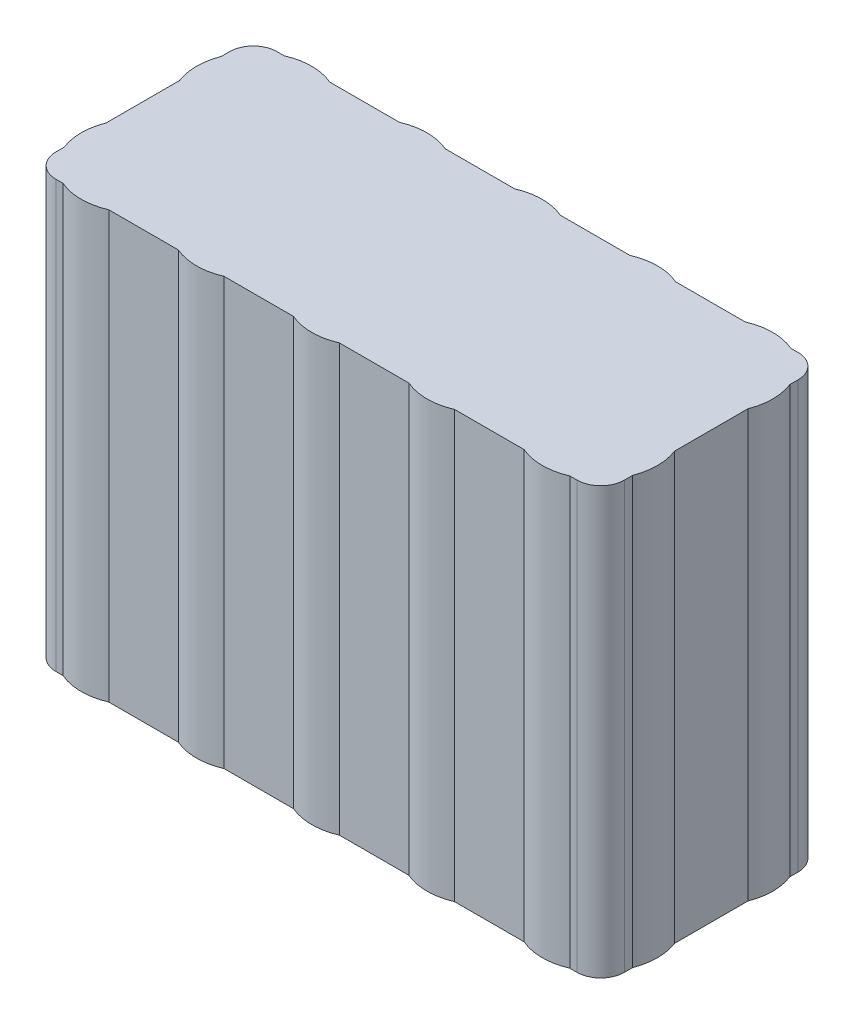
SolidWorks part; units mm, degrees
material "Gray Cast Iron"
ref_plane "Front" through (0, 0, 0) normal (0, 0, 1) x (1, 0, 0)
ref_plane "Top" through (0, 0, 0) normal (0, 1, 0) x (1, 0, 0)
ref_plane "Right" through (0, 0, 0) normal (1, 0, 0) x (0, 0, -1)
sketch "Sketch1" plane through (0, 0, 0) normal (0, 1, 0) x (1, 0, 0)
  line L0 (-27.8306, -10.7806) -> (30.5694, -10.7806) construction
  line L6 (-31.6306, -17.4806) -> (34.3694, -17.4806)
  line L7 (30.5694, -10.7806) -> (30.5694, 3.8194) construction
  line L8 (30.5694, 3.8194) -> (-27.8306, 3.8194) construction
  line L9 (-27.8306, 3.8194) -> (-27.8306, -10.7806) construction
  line L10 (-34.6306, -14.4806) -> (-34.6306, 7.5194)
  line L11 (-31.6306, 10.5194) -> (34.3694, 10.5194)
  line L12 (37.3694, -14.4806) -> (37.3694, 7.5194)
  line L13 (-34.6306, -17.4806) -> (37.3694, 10.5194) construction
  line L14 (-34.6306, 10.5194) -> (37.3694, -17.4806) construction
  circle A0 centre (-27.8306, -10.7806) radius 7.3
  circle A1 centre (-13.2306, -10.7806) radius 7.3
  circle A2 centre (1.3694, -10.7806) radius 7.3
  circle A3 centre (15.9694, -10.7806) radius 7.3
  circle A4 centre (30.5694, -10.7806) radius 7.3
  circle A5 centre (30.5694, 3.8194) radius 7.3
  circle A6 centre (-27.8306, 3.8194) radius 7.3
  circle A7 centre (-13.2306, 3.8194) radius 7.3
  circle A8 centre (1.3694, 3.8194) radius 7.3
  circle A9 centre (15.9694, 3.8194) radius 7.3
  arc A10 (-34.6306, -14.4806) -> (-31.6306, -17.4806) centre (-31.6306, -14.4806) ccw
  arc A11 (34.3694, -17.4806) -> (37.3694, -14.4806) centre (34.3694, -14.4806) ccw
  arc A12 (37.3694, 7.5194) -> (34.3694, 10.5194) centre (34.3694, 7.5194) ccw
  arc A13 (-34.6306, 7.5194) -> (-31.6306, 10.5194) centre (-31.6306, 7.5194) cw
  point P0 (0, 0)
  point P1 (1.3694, -3.4806)
  dimension "D3" = 14.6
  dimension "D13" = 72
  dimension "D14" = 3
  dimension "D15" = 3
  dimension "D16" = 3
  dimension "D17" = 3
  dimension "D2" = 28
  dimension "D4" = 14.6
  dimension "D5" = 14.6
  dimension "D6" = 14.6
  dimension "D7" = 14.6
  dimension "D8" = 14.6
  dimension "D9" = 14.6
  dimension "D10" = 14.6
  dimension "D11" = 14.6
  dimension "D12" = 14.6
extrude "Boss-Extrude1" add sketch "Sketch1" along normal blind 54 contours A6 L11 L10 | A13 L10 A6 L11 | A6 L10 A0 | A1 | A2 | A3 | A4 | A5 | A9 | A8 | A7
